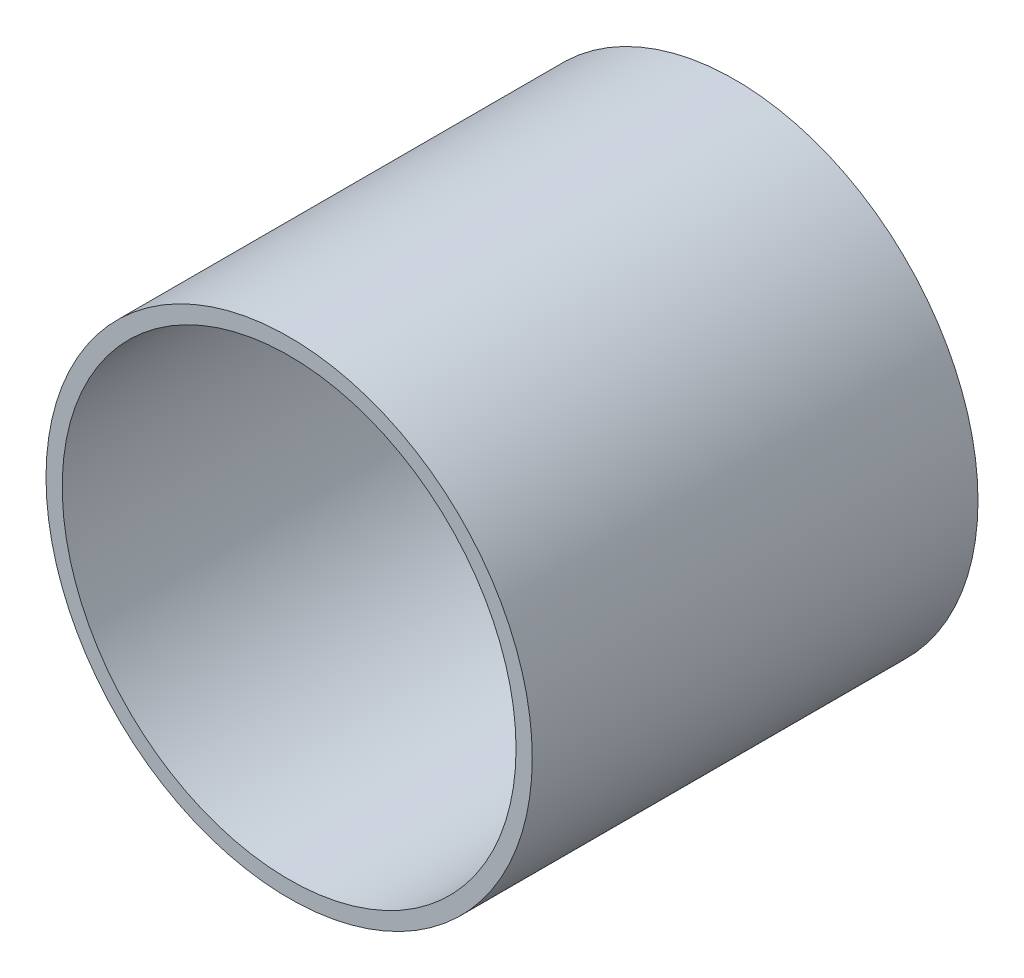
SolidWorks part; units mm, degrees
ref_plane "Front Plane" through (0, 0, 0) normal (0, 0, 1) x (1, 0, 0)
ref_plane "Top Plane" through (0, 0, 0) normal (0, 1, 0) x (1, 0, 0)
ref_plane "Right Plane" through (0, 0, 0) normal (1, 0, 0) x (0, 0, -1)
sketch "Sketch1" plane through (0, 0, 0) normal (0, 0, 1) x (1, 0, 0)
  circle A0 centre (0, 0) radius 3.81
  dimension "D1" = 7.62
extrude "Boss-Extrude1" add sketch "Sketch1" along normal mid plane 6.985 contours A0
sketch "Sketch2" plane through (0, 0, 3.4925) normal (0, 0, 1) x (1, 0, 0)
  circle A0 centre (0, 0) radius 3.556
  dimension "D1" = 7.112
extrude "Cut-Extrude1" cut sketch "Sketch2" against normal through all
